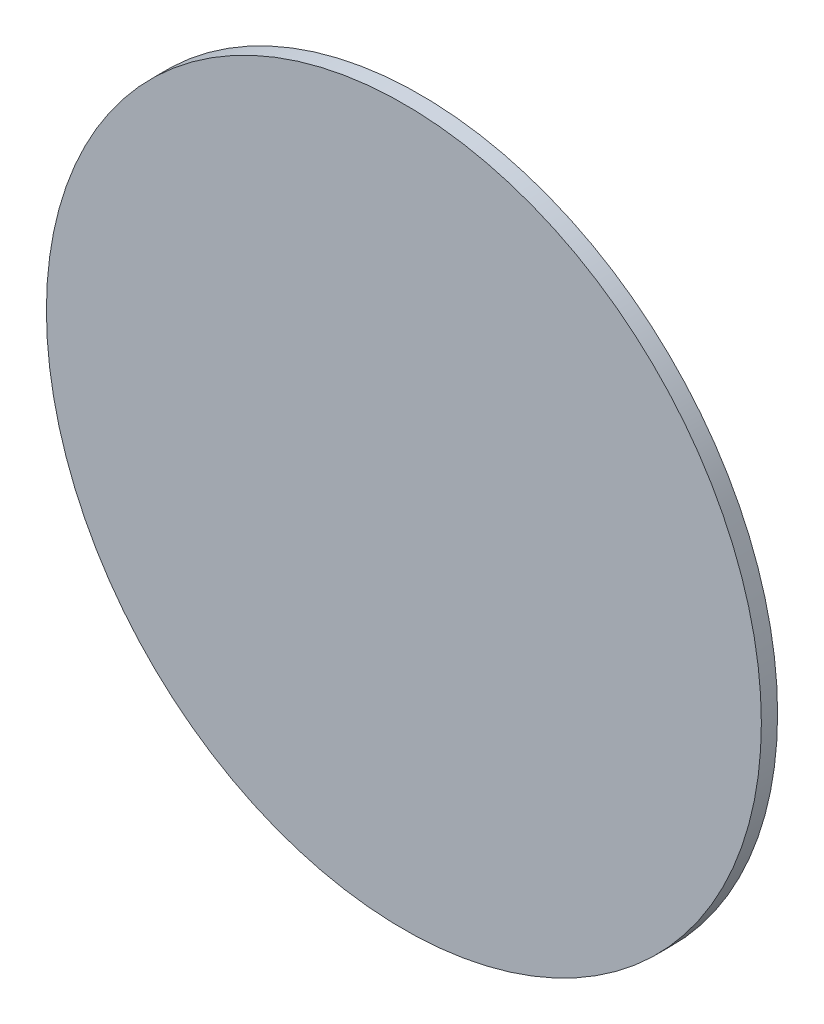
SolidWorks part; units mm, degrees
ref_plane "Front Plane" through (0, 0, 0) normal (0, 0, 1) x (1, 0, 0)
ref_plane "Top Plane" through (0, 0, 0) normal (0, 1, 0) x (1, 0, 0)
ref_plane "Right Plane" through (0, 0, 0) normal (1, 0, 0) x (0, 0, -1)
sketch "Sketch1" plane through (0, 0, 0) normal (0, 0, 1) x (1, 0, 0)
  circle A0 centre (0, 0) radius 22.025
  dimension "D1" = 44.05
extrude "Boss-Extrude1" add sketch "Sketch1" along normal blind 1
